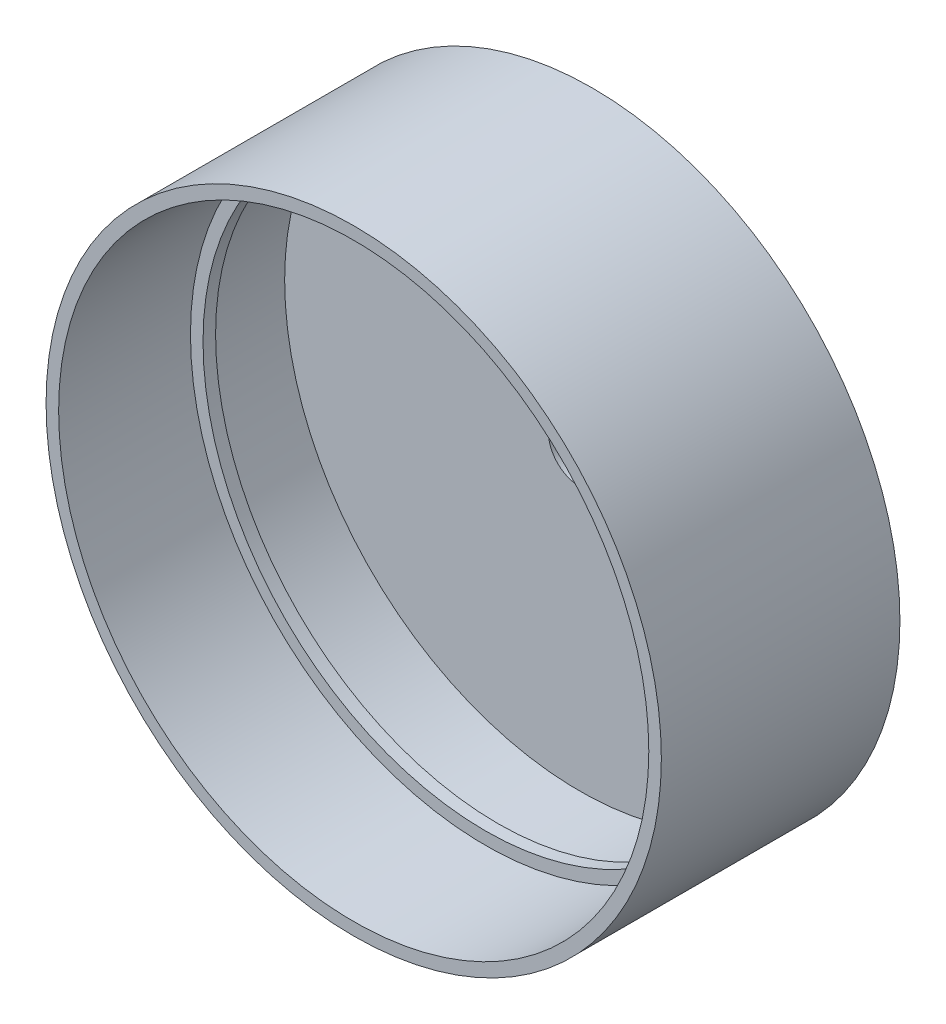
SolidWorks part; units mm, degrees
material "ABS"
ref_plane "Alzado" through (0, 0, 0) normal (0, 0, 1) x (1, 0, 0)
ref_plane "Planta" through (0, 0, 0) normal (0, 1, 0) x (1, 0, 0)
ref_plane "Vista lateral" through (0, 0, 0) normal (1, 0, 0) x (0, 0, -1)
sketch "Croquis1" plane through (0, 0, 0) normal (0, 0, 1) x (1, 0, 0)
  circle A0 centre (0, 0) radius 49
  circle A1 centre (0, 0) radius 47
  dimension "D1" = 98
  dimension "D2" = 94
extrude "Saliente-Extruir1" add sketch "Croquis1" along normal blind 38
sketch "Croquis2" plane through (0, 0, 0) normal (0, 0, 1) x (1, 0, 0)
  circle A0 centre (0, 0) radius 49
  circle A1 centre (0, 0) radius 5
  dimension "D1" = 10
extrude "Saliente-Extruir3" add sketch "Croquis2" along normal blind 2
sketch "Croquis3" plane through (0, 0, 0) normal (0, 0, 1) x (1, 0, 0)
  circle A0 centre (0, 0) radius 49
  circle A1 centre (0, 0) radius 45
  dimension "D1" = 90
extrude "Saliente-Extruir4" add sketch "Croquis3" along normal blind 2 from offset 15
